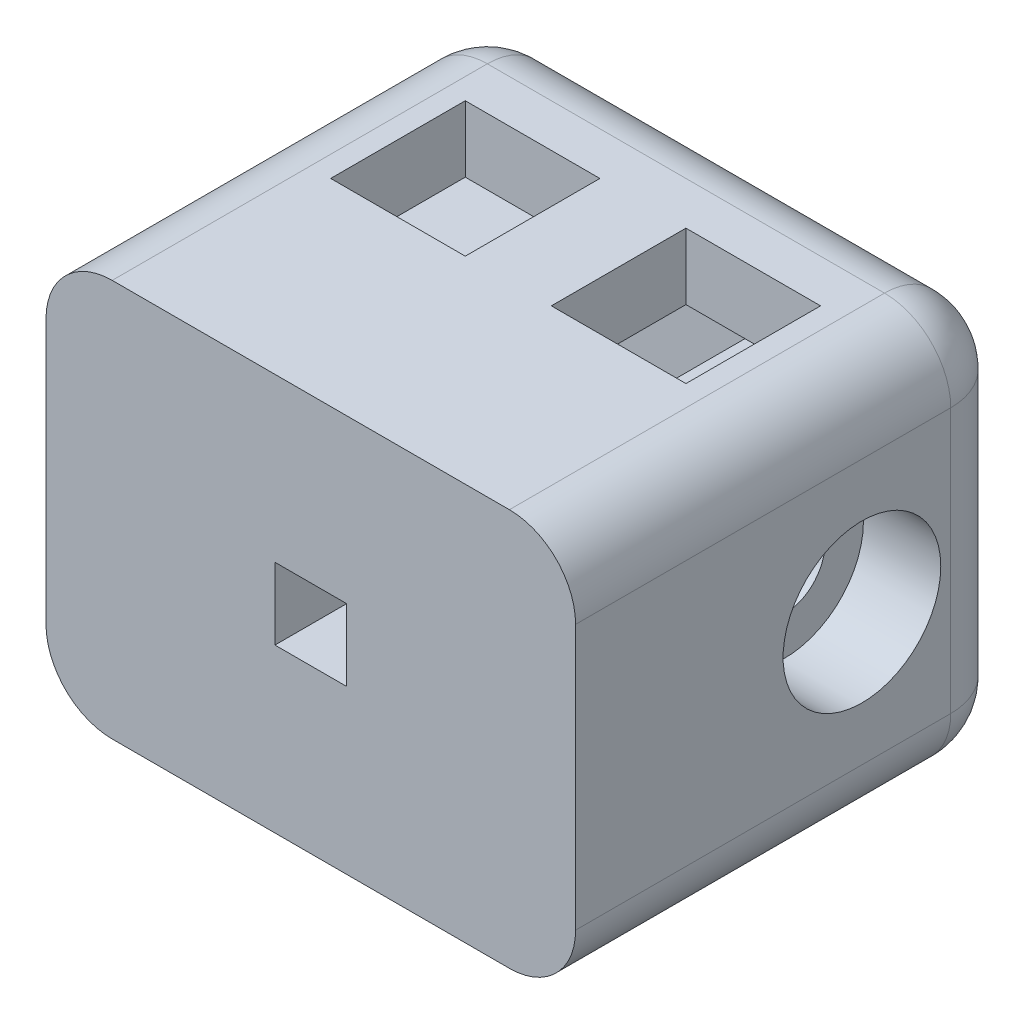
SolidWorks part; units mm, degrees
material "ABS"
ref_plane "Front Plane" through (0, 0, 0) normal (0, 0, 1) x (1, 0, 0)
ref_plane "Top Plane" through (0, 0, 0) normal (0, 1, 0) x (1, 0, 0)
ref_plane "Right Plane" through (0, 0, 0) normal (1, 0, 0) x (0, 0, -1)
sketch "Sketch1" plane through (0, 0, 0) normal (0, 0, 1) x (1, 0, 0)
  line L1 (-1.625, 1.625) -> (1.625, 1.625)
  line L2 (-1.625, 1.625) -> (-1.625, -1.625)
  line L3 (-1.625, -1.625) -> (1.625, -1.625)
  line L4 (1.625, 1.625) -> (1.625, -1.625)
  line L5 (-1.625, 1.625) -> (1.625, -1.625) construction
  line L6 (-1.625, -1.625) -> (1.625, 1.625) construction
  line L7 (-12, -9) -> (12, -9)
  line L8 (-12, -9) -> (-12, 9)
  line L9 (-12, 9) -> (12, 9)
  line L10 (12, -9) -> (12, 9)
  line L11 (-12, -9) -> (12, 9) construction
  line L12 (-12, 9) -> (12, -9) construction
  line L13 (-1.625, 4) -> (-4.8, 4)
  line L14 (-1.625, 4) -> (-1.625, -4)
  line L15 (-1.625, -4) -> (-4.8, -4)
  line L16 (-4.8, 4) -> (-4.8, -4)
  point P0 (0, 0)
  point P5 (0, 0)
  point P15 (-1.625, 0)
  dimension "D1" = 3.25
  dimension "D2" = 18
  dimension "D3" = 24
  dimension "D4" = 8
  dimension "D5" = 3.175
extrude "Boss-Extrude1" add sketch "Sketch1" along normal blind 20 contours L7 L10 L9 L8 L1 L4 L3 L2 | L13 L16 L15 L14 L2
fillet "Fillet1" radius 3 8 edges at (12, 0, 0) (-12, 0, 0) (0, -9, 0) (-12, -9, 10) (-12, 9, 10) (12, -9, 10) (0, 9, 0) (12, 9, 10)
sketch "Sketch2" plane through (0, 9, 0) normal (0, 1, 0) x (1, 0, 0)
  line L0 (0, 0) -> (0, -20) construction
  line L1 (-8.05, -11.05) -> (-1.95, -11.05)
  line L2 (-8.05, -11.05) -> (-8.05, -4.95)
  line L3 (-8.05, -4.95) -> (-1.95, -4.95)
  line L4 (-1.95, -11.05) -> (-1.95, -4.95)
  line L5 (-8.05, -11.05) -> (-1.95, -4.95) construction
  line L6 (-8.05, -4.95) -> (-1.95, -11.05) construction
  line L7 (-9, -20) -> (9, -20) construction
  line L8 (0, -8) -> (-5, -8) construction
  line L9 (-5, -8) -> (-5, -3) construction
  line L10 (9, -3) -> (-9, -3) construction
  line L11 (8.05, -4.95) -> (1.95, -11.05) construction
  line L12 (8.05, -11.05) -> (1.95, -4.95) construction
  line L13 (1.95, -11.05) -> (1.95, -4.95)
  line L14 (8.05, -4.95) -> (1.95, -4.95)
  line L15 (8.05, -11.05) -> (8.05, -4.95)
  line L16 (8.05, -11.05) -> (1.95, -11.05)
  point P0 (-5, -8)
  point P19 (5, -8)
  dimension "D1" = 6.1
  dimension "D2" = 5
  dimension "D3" = 5
extrude "Cut-Extrude1" cut sketch "Sketch2" against normal blind 3
sketch "Sketch3" plane through (0, 6, 0) normal (0, 1, 0) x (1, 0, 0)
  line L1 (-4.625, -2.95) -> (4.625, -2.95)
  line L2 (-4.625, -2.95) -> (-4.625, -11.05)
  line L3 (-4.625, -11.05) -> (4.625, -11.05)
  line L4 (4.625, -2.95) -> (4.625, -11.05)
  line L5 (1.95, -11.05) -> (8.05, -11.05) construction
  line L6 (-1.95, -8) -> (-4.625, -8) construction
  line L7 (-1.95, -11.05) -> (-1.95, -4.95) construction
  line L8 (1.95, -8) -> (4.625, -8) construction
  line L9 (1.95, -4.95) -> (1.95, -11.05) construction
  line L13 (1.625, 0) -> (-1.625, 0)
  line L14 (-1.625, 0) -> (-1.625, -20)
  line L15 (-1.625, -20) -> (1.625, -20)
  line L16 (1.625, -20) -> (1.625, 0)
  line L17 (1.625, 0) -> (-1.625, 0) construction
  line L18 (-1.625, 0) -> (-1.625, -20) construction
  line L19 (-1.625, -20) -> (1.625, -20) construction
  line L20 (1.625, -20) -> (1.625, 0) construction
  dimension "D1" = 3
  dimension "D2" = 8.1
  dimension "D3" = 0
extrude "Cut-Extrude2" cut sketch "Sketch3" against normal through all
sketch "Sketch4" plane through (0, 0, 0) normal (0, 0, -1) x (-1, 0, 0)
  line L0 (1.625, 1.625) -> (-1.625, 1.625) construction
  line L1 (1.625, -1.625) -> (-1.625, -1.625) construction
  line L2 (-1.625, 1.625) -> (-1.625, -1.625) construction
  line L3 (1.625, 1.625) -> (1.625, -1.625) construction
  line L4 (1.625, 1.625) -> (-1.625, 1.625)
  line L5 (1.625, -1.625) -> (-1.625, -1.625)
  line L6 (-1.625, 1.625) -> (-1.625, -1.625)
  line L7 (1.625, 1.625) -> (1.625, -1.625)
extrude "Boss-Extrude2" add sketch "Sketch4" against normal up to surface (2.95 mm away) up to face at (0, 0, 2.95)
sketch "Sketch5" plane through (12, 0, 0) normal (1, 0, 0) x (0, 0, -1)
  line L0 (-20, 1.625) -> (-11.05, 1.625) construction
  line L1 (-11.05, 1.625) -> (-11.05, -1.625) construction
  line L2 (-11.05, -1.625) -> (-20, -1.625) construction
  line L3 (-20, -1.625) -> (-20, 1.625) construction
  line L4 (-3, -9) -> (-11.05, -9) construction
  line L5 (-11.05, -9) -> (-11.05, 6) construction
  line L6 (-11.05, 6) -> (-4.95, 6) construction
  line L7 (-4.95, 6) -> (-2.95, 6) construction
  line L8 (-2.95, 6) -> (-2.95, -8.9996) construction
  line L9 (-20, 1.625) -> (-11.05, 1.625) construction
  line L10 (-11.05, 1.625) -> (-11.05, -1.625) construction
  line L11 (-11.05, -1.625) -> (-20, -1.625) construction
  line L12 (-20, -1.625) -> (-20, 1.625) construction
  line L13 (-3, -9) -> (-11.05, -9) construction
  line L14 (-11.05, -9) -> (-11.05, 6) construction
  line L15 (-11.05, 6) -> (-4.95, 6) construction
  line L16 (-4.95, 6) -> (-2.95, 6) construction
  line L17 (-2.95, 6) -> (-2.95, -8.9996) construction
  line L18 (-11.05, 0) -> (-7.025, 0)
  line L19 (-7.025, 0) -> (-7.025, -9)
  arc A0 (-3, -9) -> (-2.95, -8.9996) centre (-3, -6) ccw construction
  arc A1 (-3, -9) -> (-2.95, -8.9996) centre (-3, -6) ccw construction
hole_wizard "CBORE for #6 Socket Head Cap Screw1" positions "Sketch7" profile "Sketch6" counterbore size "#6" standard "ANSI Inch" end condition through all
sketch "Sketch7" plane through (12, 0, 0) normal (1, 0, 0) x (0, 0, -1)
  point P0 (-7.025, 0)
sketch "Sketch6" plane through (12, 0, 7.025) normal (0, 1, 0) x (0, 0, -1)
  line L0 (0, 0) -> (0, 24)
  line L1 (0, 24) -> (1.8288, 24)
  line L3 (1.8288, 24) -> (1.8288, 3.5052)
  line L4 (1.8288, 3.5052) -> (3.5725, 3.5052)
  line L5 (3.5725, 3.5052) -> (3.5725, 0)
  line L7 (3.5725, 0) -> (0, 0)
  line L11 (0, -6.35) -> (0, 107.95) construction
  dimension "Thru Hole Dia." = 3.6576
  dimension "Thru Hole Depth" = 24
  dimension "C'Bore Dia." = 7.145
  dimension "C'Bore Depth" = 3.5052
